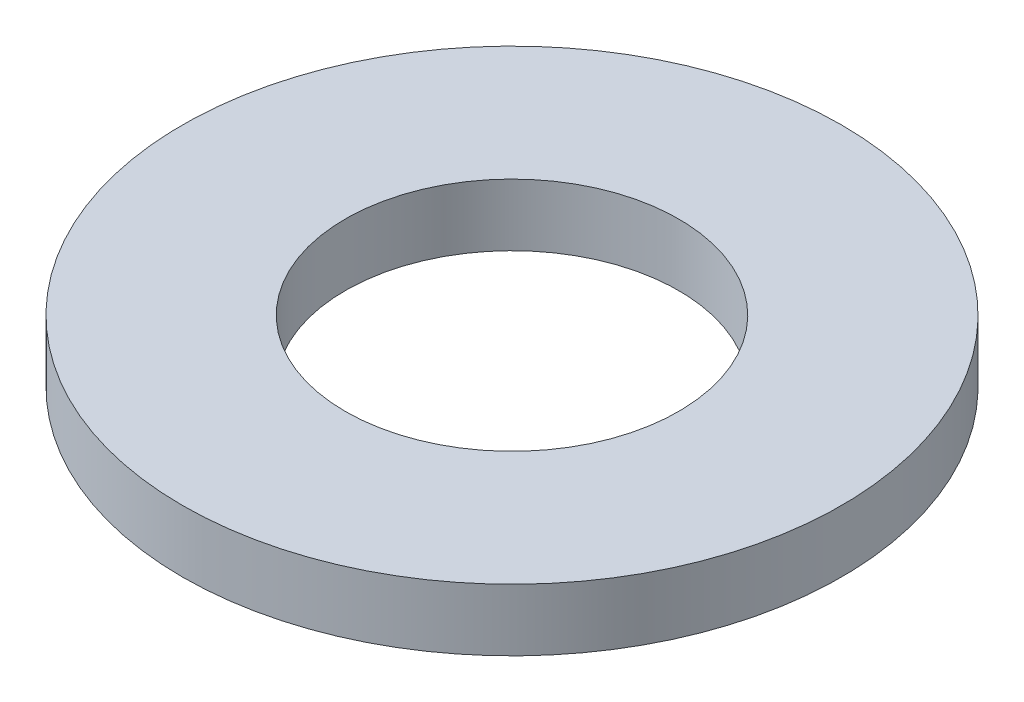
SolidWorks part; units mm, degrees
ref_plane "前视基准面" through (0, 0, 0) normal (0, 0, 1) x (1, 0, 0)
ref_plane "上视基准面" through (0, 0, 0) normal (0, 1, 0) x (1, 0, 0)
ref_plane "右视基准面" through (0, 0, 0) normal (1, 0, 0) x (0, 0, -1)
sketch "草图1" plane through (0, 0, 0) normal (0, 1, 0) x (1, 0, 0)
  circle A0 centre (0, 0) radius 2.15
  circle A1 centre (0, 0) radius 4.25
  dimension "D1" = 4.3
  dimension "D2" = 8.5
extrude "凸台-拉伸1" add sketch "草图1" along normal blind 0.8
